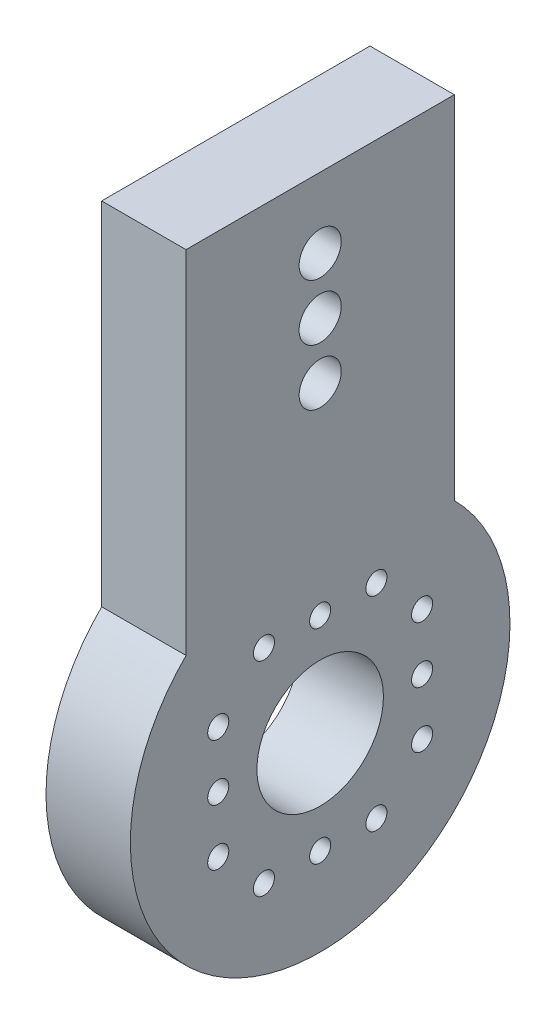
SolidWorks part; units mm, degrees
ref_plane "Front Plane" through (0, 0, 0) normal (0, 0, 1) x (1, 0, 0)
ref_plane "Top Plane" through (0, 0, 0) normal (0, 1, 0) x (1, 0, 0)
ref_plane "Right Plane" through (0, 0, 0) normal (1, 0, 0) x (0, 0, -1)
sketch "Sketch1" plane through (0, 0, 0) normal (1, 0, 0) x (0, 0, -1)
  line L0 (-17.6377, 0) -> (28.955, 0) construction
  line L1 (0, 0) -> (21.8867, 21.8867) construction
  line L2 (0, 0) -> (-17.8374, 17.8374) construction
  line L5 (-9.5426, 9.5493) -> (-9.5426, 34.5493)
  line L6 (-9.5426, 34.5493) -> (9.5426, 34.5493)
  line L7 (9.5426, 9.5493) -> (9.5426, 34.5493)
  arc A0 (-9.5426, 9.5493) -> (9.5426, 9.5493) centre (0, 0) ccw
  circle A1 centre (0, 0) radius 4.5
  circle A2 centre (0, 7.25) radius 0.75
  circle A3 centre (4, 7.25) radius 0.75
  circle A4 centre (-4, 7.25) radius 0.75
  circle A5 centre (4, -7.25) radius 0.75
  circle A6 centre (0, -7.25) radius 0.75
  circle A7 centre (-4, -7.25) radius 0.75
  circle A8 centre (7.25, -4) radius 0.75
  circle A9 centre (7.25, 0) radius 0.75
  circle A10 centre (7.25, 4) radius 0.75
  circle A11 centre (-7.25, 4) radius 0.75
  circle A12 centre (-7.25, 0) radius 0.75
  circle A13 centre (-7.25, -4) radius 0.75
  circle A14 centre (0, 29.5493) radius 1.5
  circle A15 centre (0, 25.5493) radius 1.5
  circle A16 centre (0, 21.5493) radius 1.4983
  point P42 (0, 0)
  point P43 (0, 29.4343)
  dimension "D1" = 27
  dimension "D2" = 9
  dimension "D4" = 1.5
  dimension "D10" = 3
  dimension "D11" = 3
  dimension "D12" = 2.9965
  dimension "D3" = 7.25
  dimension "D5" = 4
  dimension "D6" = 4
  dimension "D7" = 45
  dimension "D8" = 45
  dimension "D9" = 25
  dimension "D13" = 5
  dimension "D14" = 4
  dimension "D15" = 4
extrude "Boss-Extrude1" add sketch "Sketch1" along normal blind 6
